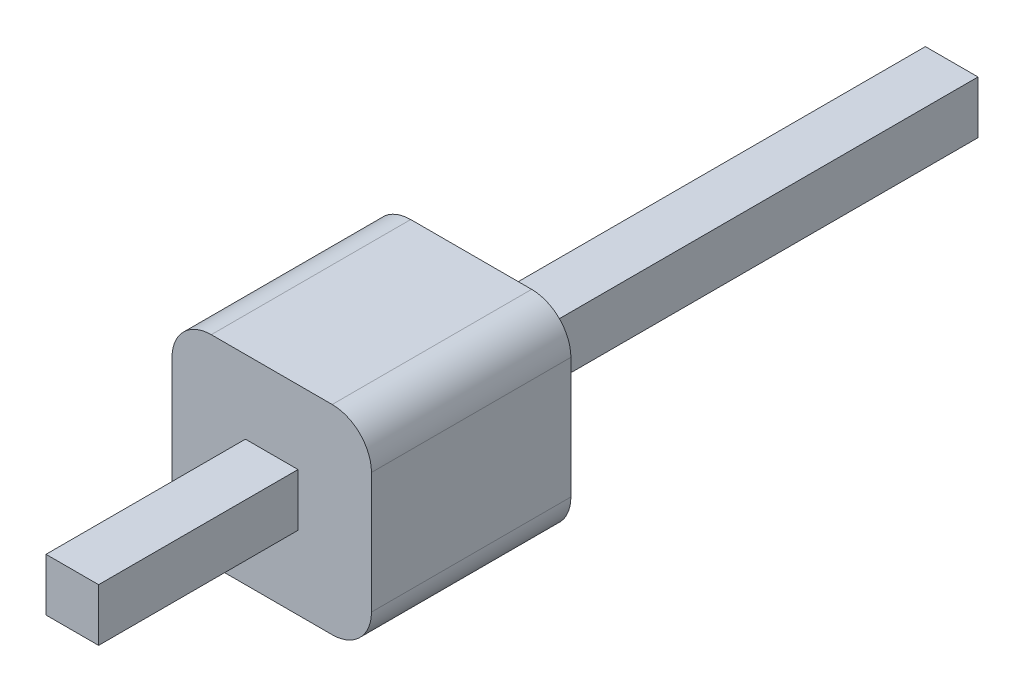
SolidWorks part; units mm, degrees
ref_plane "前视基准面" through (0, 0, 0) normal (0, 0, 1) x (1, 0, 0)
ref_plane "上视基准面" through (0, 0, 0) normal (0, 1, 0) x (1, 0, 0)
ref_plane "右视基准面" through (0, 0, 0) normal (1, 0, 0) x (0, 0, -1)
sketch "草图1" plane through (0, 0, 0) normal (0, 0, 1) x (1, 0, 0)
  line L0 (0, 5.3599) -> (0, -8.0108) construction
  line L1 (-1.27, 1.27) -> (1.27, 1.27)
  line L2 (-1.27, 1.27) -> (-1.27, -1.27)
  line L3 (-1.27, -1.27) -> (1.27, -1.27)
  line L4 (1.27, 1.27) -> (1.27, -1.27)
  line L5 (-4.807, 0) -> (4.5413, 0) construction
  dimension "D1" = 2.54
  dimension "D2" = 2.54
extrude "拉伸1" add sketch "草图1" along normal blind 2.54
ref_plane "基准面1" through (0, 0, 5.08) normal (0, 0, -1) x (-1, 0, 0)
sketch "草图2" plane through (0, 0, 5.08) normal (0, 0, -1) x (-1, 0, 0)
  line L0 (-1.27, 0) -> (1.27, 0) construction
  line L1 (-1.27, -1.27) -> (-1.27, 1.27) construction
  line L2 (1.27, 1.27) -> (1.27, -1.27) construction
  line L3 (0, 1.9407) -> (0, -4.2425) construction
  line L5 (-0.335, 0.335) -> (0.335, 0.335)
  line L6 (-0.335, 0.335) -> (-0.335, -0.335)
  line L7 (-0.335, -0.335) -> (0.335, -0.335)
  line L8 (0.335, 0.335) -> (0.335, -0.335)
  dimension "D1" = 0.67
  dimension "D2" = 0.67
sketch "草图3" plane through (0, 0, 0) normal (1, 0, 0) x (0, 0, -1)
  line L0 (6.12, -0.01) -> (-5.08, -0.01)
  line L1 (-5.08, 1.9407) -> (-5.08, -4.2425) construction
  line L8 (-2.54, 1.27) -> (0, 1.27) construction
  line L9 (0, -1.27) -> (0, 1.27) construction
  point P11 (2.54, -1.2991)
  dimension "D1" = 5.08
  dimension "D2" = 11.2
  dimension "D4" = 1.28
sweep "扫描1" add profiles "草图2" path "草图3"
fillet "圆角1" radius 0.5 4 edges at (1.27, 1.27, 1.27) (1.27, -1.27, 1.27) (-1.27, -1.27, 1.27) (-1.27, 1.27, 1.27)
